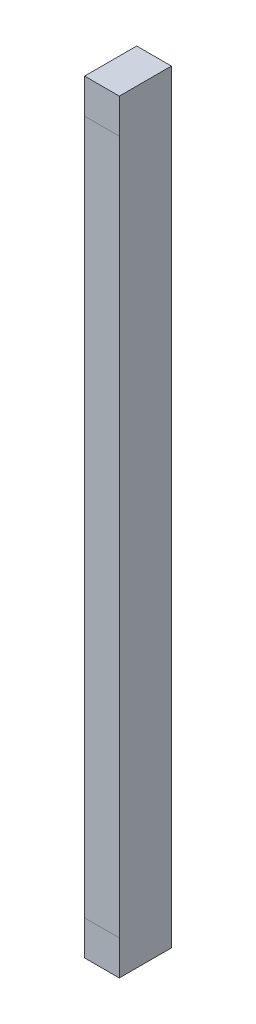
SolidWorks part; units mm, degrees
ref_plane "Płaszczyzna przednia" through (0, 0, 0) normal (0, 0, 1) x (1, 0, 0)
ref_plane "Płaszczyzna górna" through (0, 0, 0) normal (0, 1, 0) x (1, 0, 0)
ref_plane "Płaszczyzna prawa" through (0, 0, 0) normal (1, 0, 0) x (0, 0, -1)
sketch "Szkic1" plane through (0, 0, 0) normal (0, 1, 0) x (1, 0, 0)
  line L1 (0, 0) -> (100, 0)
  line L2 (0, 0) -> (0, 150)
  line L3 (0, 150) -> (100, 150)
  line L4 (100, 0) -> (100, 150)
  dimension "D1" = 100
  dimension "D2" = 150
extrude "Dodanie-wyciągnięcie1" add sketch "Szkic1" along normal blind 2200
sketch "Szkic2" plane through (0, 0, 0) normal (0, 0, 1) x (1, 0, 0)
  line L0 (0, 2100) -> (100, 2100)
  line L1 (0, 2200) -> (0, 0) construction
  line L2 (100, 2200) -> (100, 0) construction
  line L3 (0, 100) -> (100, 100)
  line L4 (0, 2200) -> (100, 2200) construction
  line L5 (0, 0) -> (100, 0) construction
  dimension "D1" = 100
  dimension "D2" = 100
split line "Linia podziałowa1"
